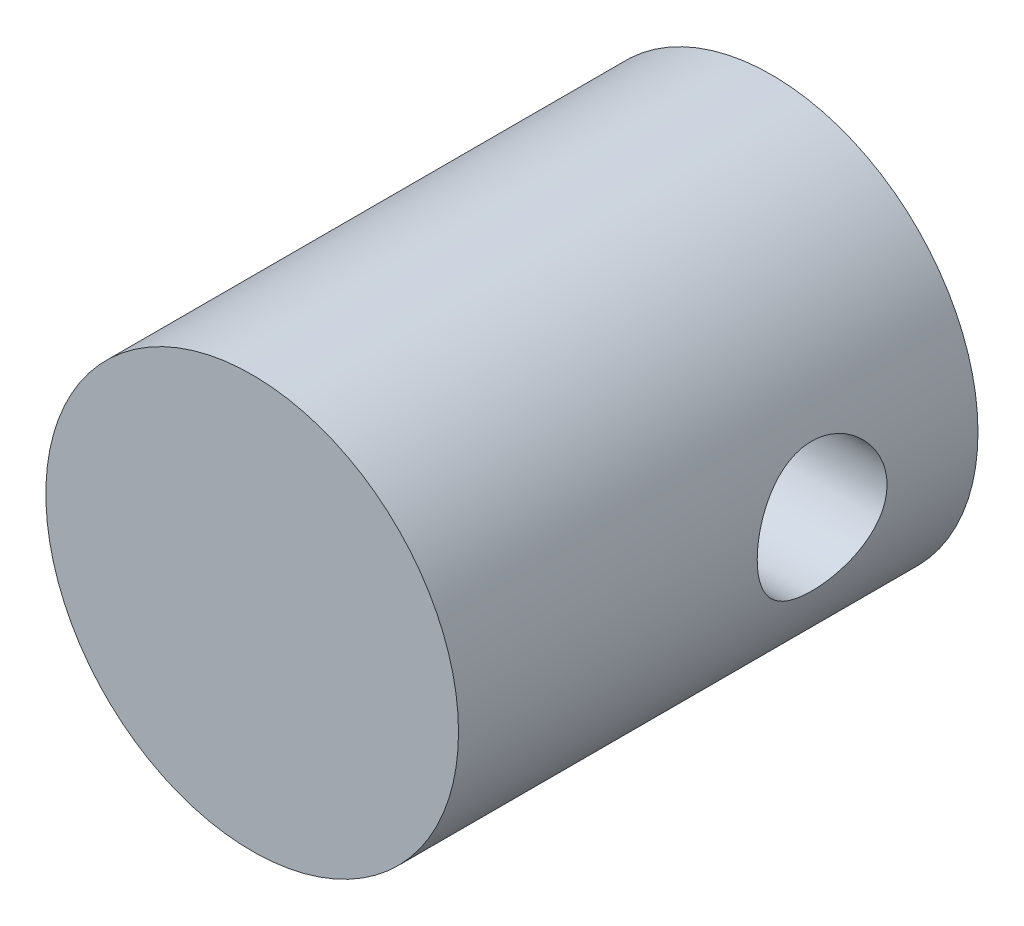
SolidWorks part; units mm, degrees
ref_plane "Front Plane" through (0, 0, 0) normal (1, 0, 0) x (0, 1, 0)
ref_plane "Top Plane" through (0, 0, 0) normal (0, 0, 1) x (0, 1, 0)
ref_plane "Right Plane" through (0, 0, 0) normal (0, 1, 0) x (-1, 0, 0)
sketch "Sketch1" plane through (0, 0, 0) normal (0, 0, 1) x (0, 1, 0)
  circle A0 centre (0, 0) radius 12.6111
  dimension "D1" = 25.2222
extrude "Boss-Extrude1" add sketch "Sketch1" along normal blind 31.75
sketch "Sketch2" plane through (0, 0, 0) normal (1, 0, 0) x (0, 1, 0)
  line L0 (0, 0) -> (0, 9.525) construction
  line L1 (0, 9.525) -> (0, 31.75) construction
  line L2 (12.6111, 31.75) -> (-12.6111, 31.75) construction
  circle A0 centre (0, 9.525) radius 3.9688
  dimension "D1" = 7.9375
  dimension "D2" = 9.525
extrude "Cut-Extrude1" cut sketch "Sketch2" against normal through all both and the other way through all
